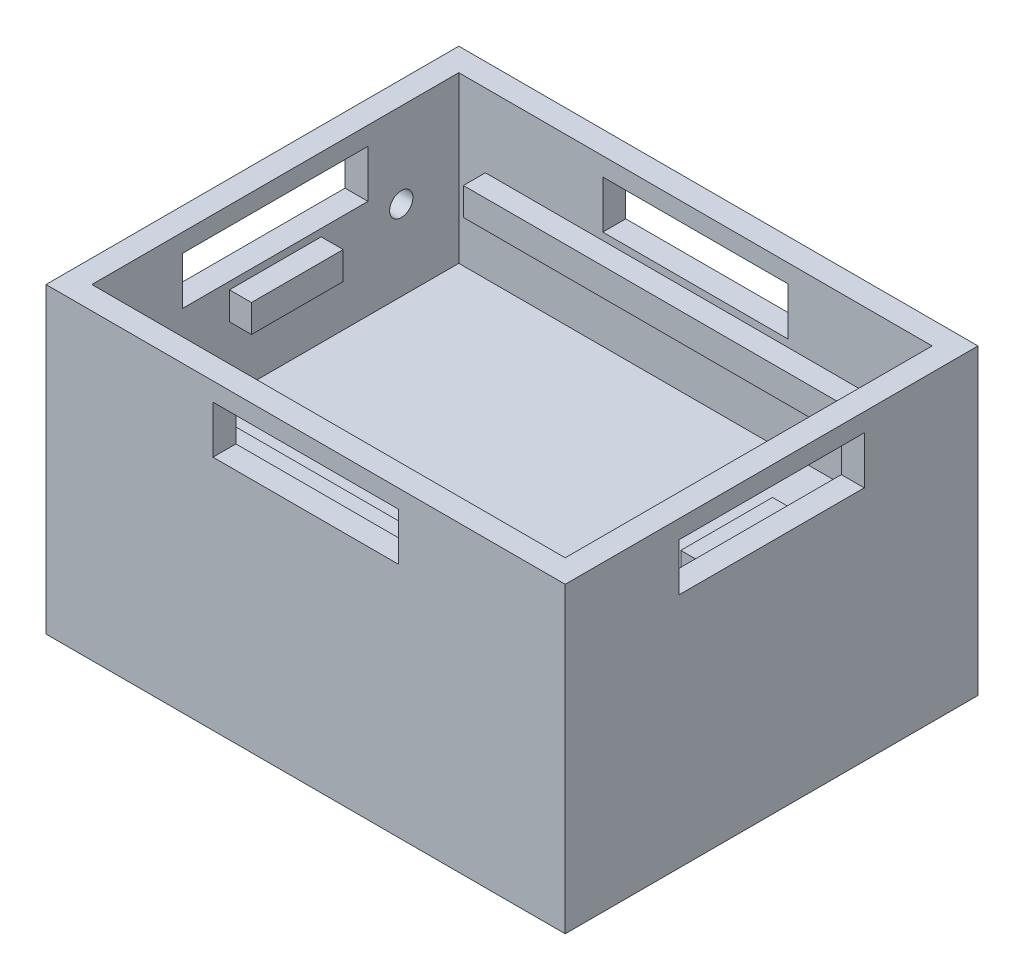
SolidWorks part; units mm, degrees
ref_plane "Front Plane" through (0, 0, 0) normal (0, 0, 1) x (1, 0, 0)
ref_plane "Top Plane" through (0, 0, 0) normal (0, 1, 0) x (1, 0, 0)
ref_plane "Right Plane" through (0, 0, 0) normal (1, 0, 0) x (0, 0, -1)
sketch "Sketch1" plane through (0, 0, 0) normal (0, 1, 0) x (1, 0, 0)
  line L0 (-2.5, 2.5) -> (-2.5, 202.5)
  line L5 (-15, -10) -> (268, -10)
  line L6 (-15, -10) -> (-15, 215)
  line L7 (-15, 215) -> (268, 215)
  line L8 (268, -10) -> (268, 215)
  line L9 (-2.5, 202.5) -> (255.5, 202.5)
  line L10 (255.5, 2.5) -> (255.5, 202.5)
  line L11 (-2.5, 2.5) -> (255.5, 2.5)
  dimension "D1" = 283
  dimension "D2" = 225
  dimension "D3" = 12.5
extrude "Walls" add sketch "Sketch1" along normal blind 90
sketch "Sketch3" plane through (0, 0, 0) normal (0, -1, 0) x (1, 0, 0)
  line L0 (268, -215) -> (-15, -215) construction
  line L1 (268, 10) -> (268, -215) construction
  line L2 (-15, 10) -> (268, 10) construction
  line L3 (-15, -215) -> (-15, 10) construction
  line L4 (268, -215) -> (-15, -215)
  line L5 (268, 10) -> (268, -215)
  line L6 (-15, 10) -> (268, 10)
  line L7 (-15, -215) -> (-15, 10)
extrude "Base" add sketch "Sketch3" along normal blind 12.5
ref_plane "Long_Support_Midplane" through (126.5, 0, 0) normal (1, 0, 0) x (0, 0, -1)
sketch "Sketch4" plane through (126.5, 0, 0) normal (1, 0, 0) x (0, 0, -1)
  line L0 (2.5, 0) -> (2.5, 90)
  line L1 (2.5, 50) -> (14.5, 50)
  line L2 (2.5, 50) -> (2.5, 34.9)
  line L3 (2.5, 34.9) -> (14.5, 34.9)
  line L4 (14.5, 50) -> (14.5, 34.9)
  line L5 (2.5, 0) -> (2.5, 90) construction
  line L6 (202.5, 50) -> (190.5, 50)
  line L7 (202.5, 50) -> (202.5, 34.9)
  line L8 (202.5, 34.9) -> (190.5, 34.9)
  line L9 (190.5, 50) -> (190.5, 34.9)
  line L14 (2.5, 0) -> (202.5, 0)
  line L15 (202.5, 0) -> (202.5, 90)
  line L16 (202.5, 90) -> (2.5, 90)
  line L17 (2.5, 90) -> (2.5, 0)
  line L18 (2.5, 0) -> (202.5, 0) construction
  line L19 (202.5, 0) -> (202.5, 90) construction
  line L20 (202.5, 90) -> (2.5, 90) construction
  line L21 (2.5, 90) -> (2.5, 0) construction
  dimension "D1" = 15.1
  dimension "D2" = 12
  dimension "D4" = 50
  dimension "D3" = 0
extrude "Long_Support" add sketch "Sketch4" along normal mid plane 229
ref_plane "Short_Support_Midplane" through (0, 0, -102.5) normal (0, 0, -1) x (-1, 0, 0)
sketch "Sketch5" plane through (0, 0, -102.5) normal (0, 0, -1) x (-1, 0, 0)
  line L1 (-255.5, 50) -> (-243.5, 50)
  line L2 (-255.5, 50) -> (-255.5, 34.9)
  line L3 (-255.5, 34.9) -> (-243.5, 34.9)
  line L4 (-243.5, 50) -> (-243.5, 34.9)
  line L5 (2.5, 50) -> (-9.5, 50)
  line L6 (2.5, 50) -> (2.5, 34.9)
  line L7 (2.5, 34.9) -> (-9.5, 34.9)
  line L8 (-9.5, 50) -> (-9.5, 34.9)
  line L12 (-255.5, 0) -> (2.5, 0)
  line L13 (2.5, 0) -> (2.5, 90)
  line L14 (2.5, 90) -> (-255.5, 90)
  line L15 (2.5, 0) -> (2.5, 90) construction
  line L16 (-255.5, 0) -> (2.5, 0) construction
  line L20 (-255.5, 90) -> (-255.5, 0)
  line L21 (-255.5, 90) -> (-255.5, 0) construction
  line L22 (2.5, 90) -> (-255.5, 90) construction
  dimension "D4" = 50
  dimension "D3" = 0
  dimension "D1" = 12
  dimension "D2" = 15.1
extrude "Short_Support" add sketch "Sketch5" along normal mid plane 50
sketch "Sketch6" plane through (-2.5, 0, 0) normal (1, 0, 0) x (0, 0, -1)
  line L4 (2.5, 0) -> (202.5, 0)
  line L5 (202.5, 0) -> (202.5, 90)
  line L6 (202.5, 90) -> (2.5, 90)
  line L7 (2.5, 90) -> (2.5, 0)
  line L8 (2.5, 0) -> (202.5, 0) construction
  line L9 (202.5, 0) -> (202.5, 90) construction
  line L10 (202.5, 90) -> (2.5, 90) construction
  line L11 (2.5, 90) -> (2.5, 0) construction
  circle A0 centre (171.15, 43.65) radius 6.35
  dimension "D2" = 12.7
  dimension "D3" = 31.35
  dimension "D4" = 43.65
extrude "Reservoir_Outflow_Tube_Hole" cut sketch "Sketch6" against normal up to next
sketch "Sketch7" plane through (-2.5, 0, 0) normal (1, 0, 0) x (0, 0, -1)
  line L0 (127.5, 50) -> (77.5, 50) construction
  line L1 (52, 54) -> (153, 54)
  line L2 (52, 54) -> (52, 80)
  line L3 (52, 80) -> (153, 80)
  line L4 (153, 54) -> (153, 80)
  line L5 (202.5, 90) -> (2.5, 90) construction
  line L7 (102.5, 80) -> (102.5, 54) construction
  line L8 (102.5, -27.5) -> (102.5, 27.5) construction
  dimension "D1" = 4
  dimension "D2" = 10
  dimension "D3" = 26
  dimension "D4" = 101
extrude "Connector_Port_ShortSide" cut sketch "Sketch7" against normal up to surface (283 mm away)
pattern_linear "LPattern1" count 2 spacing 270.5 along (1, 0, 0) of "Connector_Port_ShortSide"
sketch "Sketch8" plane through (0, 0, -2.5) normal (0, 0, 1) x (1, 0, 0)
  line L1 (76, 54) -> (177, 54)
  line L2 (76, 54) -> (76, 80)
  line L3 (76, 80) -> (177, 80)
  line L4 (177, 54) -> (177, 80)
  line L6 (241, 50) -> (12, 50) construction
  line L7 (126.5, 80) -> (126.5, 54) construction
  line L9 (-2.5, 90) -> (255.5, 90) construction
  line L10 (126.5, -28.05) -> (126.5, 28.05) construction
  dimension "D3" = 26
  dimension "D4" = 101
  dimension "D1" = 4
  dimension "D2" = 10
extrude "Connector_Port_LongSide" cut sketch "Sketch8" along normal up to surface (225 mm away) contours L4 L3 L2 L1
pattern_linear "LPattern2" count 2 spacing 212.5 along (0, 0, -1) of "Connector_Port_LongSide"
sketch "Sketch9" plane through (0, -12.5, 0) normal (0, -1, 0) x (1, 0, 0)
  line L10 (268, -215) -> (268, 10) construction
  line L11 (-15, -215) -> (268, -215) construction
  line L12 (268, 10) -> (-15, 10) construction
  line L13 (-15, 10) -> (-15, -215) construction
  line L14 (-2.5, -202.5) -> (255.5, -202.5)
  line L15 (255.5, -202.5) -> (255.5, -2.5)
  line L16 (255.5, -2.5) -> (-2.5, -2.5)
  line L17 (-2.5, -2.5) -> (-2.5, -202.5)
  line L18 (-2.5, -202.5) -> (255.5, -202.5)
  line L19 (255.5, -202.5) -> (255.5, -2.5)
  line L20 (255.5, -2.5) -> (-2.5, -2.5)
  line L21 (-2.5, -2.5) -> (-2.5, -202.5)
  line L22 (268, -215) -> (268, 10)
  line L23 (-15, -215) -> (268, -215)
  line L24 (268, 10) -> (-15, 10)
  line L25 (-15, 10) -> (-15, -215)
  dimension "D1" = 12.5
extrude "Lower_Water_Jacket_Walls" add sketch "Sketch9" along normal blind 50
sketch "Sketch11" plane through (0, -62.5, 0) normal (0, -1, 0) x (1, 0, 0)
  line L0 (-15, -215) -> (268, -215) construction
  line L1 (268, -215) -> (268, 10) construction
  line L2 (268, 10) -> (-15, 10) construction
  line L3 (-15, 10) -> (-15, -215) construction
  line L4 (-15, -215) -> (268, -215)
  line L5 (268, -215) -> (268, 10)
  line L6 (268, 10) -> (-15, 10)
  line L7 (-15, 10) -> (-15, -215)
extrude "Lower_Water_Jacket_Bottom" add sketch "Sketch11" along normal blind 12.5
equation "\"Length\"= 283mm"
equation "\"Width\"= 225mm"
equation "\"WallThickness\"= 12.5mm"
equation "\"UpperWaterJacketThickness\"= 28mm"
equation "\"SpacerHeight\"= 80.2mm"
equation "\"PlateLength\"= 252mm"
equation "\"PlateWidth\"= 190mm"
equation "\"PlateHoleDiameter\"= 5.9mm"
equation "\"PlateHoleBottom\"= 2mm"
equation "\"PlateHoleSide\"= 1.55mm"
equation "\"PlateHoleSpacing\"= 3.1mm"
equation "\"PlateThickness\"= 1.55mm"
equation "\"D1@Sketch1\"=\"Length\""
equation "\"D2@Sketch1\"=\"Width\""
equation "\"D3@Sketch1\"=\"WallThickness\""
equation "\"ReservoirBottom\"= 12.5mm"
equation "\"D1@Base\"=\"ReservoirBottom\""
equation "\"ReservoirSupportWidth\"= 12mm"
equation "\"D2@Sketch4\"=\"ReservoirSupportWidth\""
equation "\"ReservoirSupportHeight\"= 15.1mm"
equation "\"D1@Sketch4\"=\"ReservoirSupportHeight\""
equation "\"D1@Sketch5\"=\"ReservoirSupportWidth\""
equation "\"D2@Sketch5\"=\"ReservoirSupportHeight\""
equation "\"ReservoirSupportPlacementHeight\"= 50mm"
equation "\"D4@Sketch5\"=\"ReservoirSupportPlacementHeight\""
equation "\"D4@Sketch4\"=\"ReservoirSupportPlacementHeight\""
equation "\"ReservoirHoleDiameter\"= 12.7mm"
equation "\"D2@Sketch6\"=\"ReservoirHoleDiameter\""
equation "\"ReservoirHoleRight\"= 25mm"
equation "\"D3@Sketch6\"=\"ReservoirHoleRight\"+\"ReservoirHoleDiameter\"/2"
equation "\"ReservoirHoleTop\"= \"ReservoirSupportPlacementHeight\""
equation "\"D4@Sketch6\"=\"ReservoirHoleTop\"-\"ReservoirHoleDiameter\"/2"
equation "\"ReservoirHeight\"= 90mm"
equation "\"D1@Walls\"=\"ReservoirHeight\""
equation "\"ReservoirPortBottom\"= 4mm"
equation "\"D1@Sketch7\"=\"ReservoirPortBottom\""
equation "\"ReservoirPortTop\"= 10mm"
equation "\"D2@Sketch7\"=\"ReservoirPortTop\""
equation "\"ReservoirPortWidth\"= 101mm"
equation "\"D4@Sketch7\"=\"ReservoirPortWidth\""
equation "\"D4@Sketch8\"=\"ReservoirPortWidth\""
equation "\"D1@Sketch8\"=\"ReservoirPortBottom\""
equation "\"D2@Sketch8\"=\"ReservoirPortTop\""
equation "\"D1@Sketch9\"=\"WallThickness\""
equation "\"LowerWaterJacketHeight\"= 50"
equation "\"D1@Lower_Water_Jacket_Walls\" = \"LowerWaterJacketHeight\""
equation "\"LowerWaterJacketBottomThickness\"= \"WallThickness\""
equation "\"D1@Lower_Water_Jacket_Bottom\" = \"LowerWaterJacketBottomThickness\""
